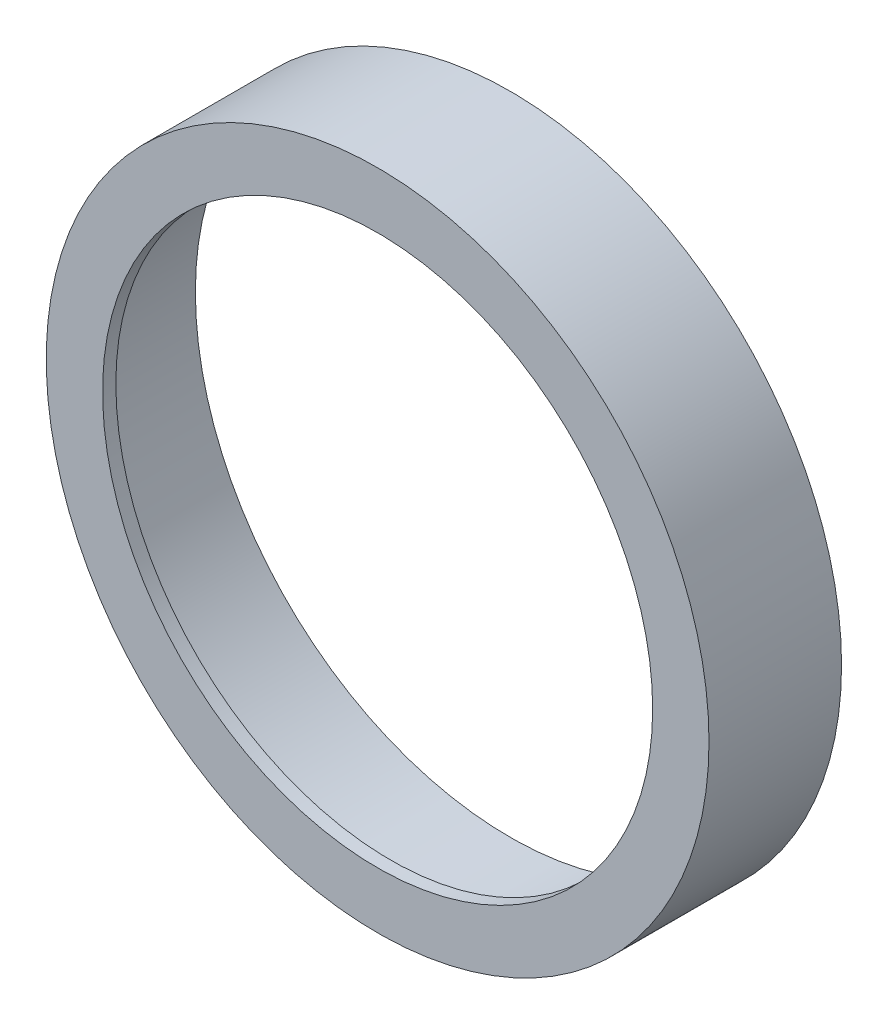
SolidWorks part; units mm, degrees
material "PC 高粘度"
ref_plane "前视基准面" through (0, 0, 0) normal (0, 0, 1) x (1, 0, 0)
ref_plane "上视基准面" through (0, 0, 0) normal (0, 1, 0) x (1, 0, 0)
ref_plane "右视基准面" through (0, 0, 0) normal (1, 0, 0) x (0, 0, -1)
sketch "草图1" plane through (0, 0, 0) normal (0, 0, 1) x (1, 0, 0)
  circle A0 centre (0, 0) radius 5
  dimension "D1" = 10
extrude "凸台-拉伸1" add sketch "草图1" along normal blind 2
sketch "草图2" plane through (0, 0, 2) normal (0, 0, 1) x (1, 0, 0)
  circle A0 centre (0, 0) radius 4.15
  dimension "D1" = 8.3
extrude "切除-拉伸1" cut sketch "草图2" against normal blind 1.8
sketch "草图3" plane through (0, 0, 0) normal (0, 0, -1) x (-1, 0, 0)
  circle A0 centre (0, 0) radius 4.75
  dimension "D1" = 9.5
extrude "切除-拉伸2" cut sketch "草图3" against normal blind 1.8
